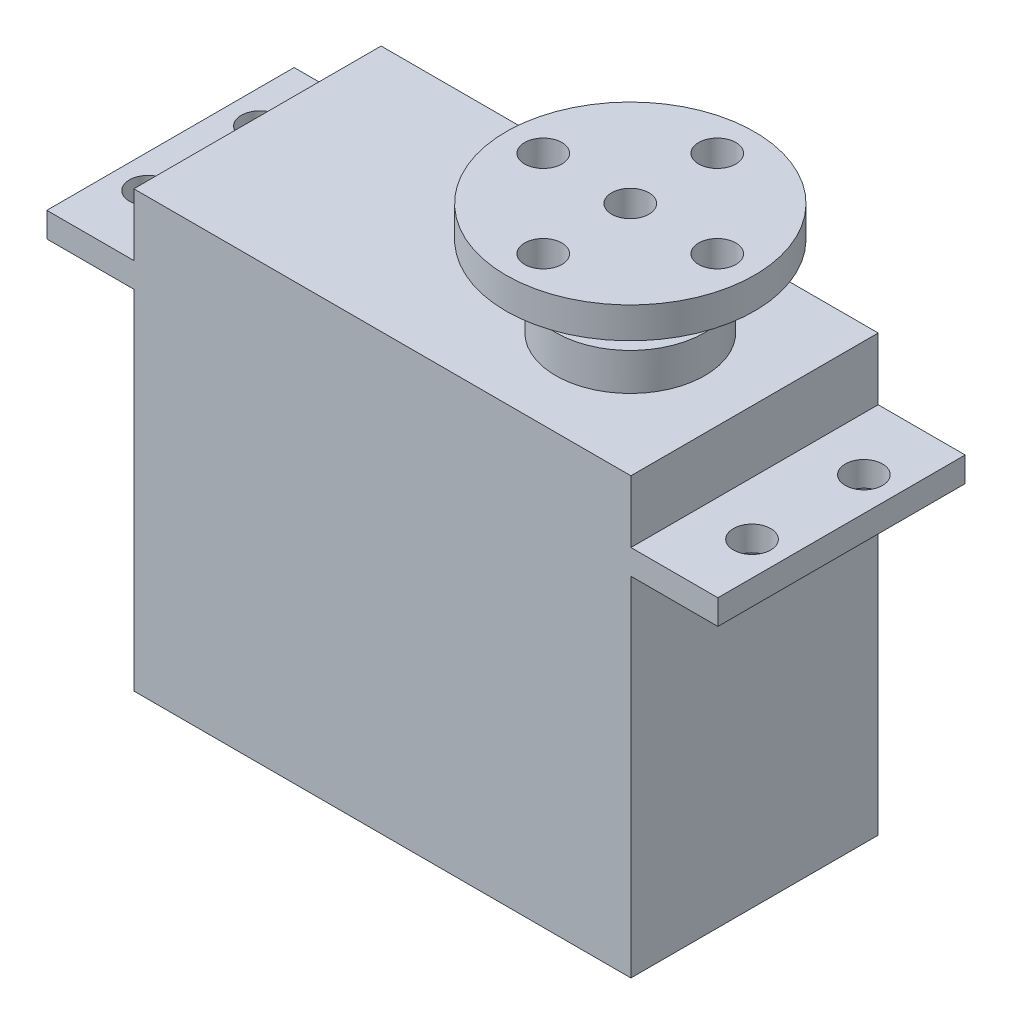
SolidWorks part; units mm, degrees
ref_plane "前视基准面" through (0, 0, 0) normal (0, 0, 1) x (1, 0, 0)
ref_plane "上视基准面" through (0, 0, 0) normal (0, 1, 0) x (1, 0, 0)
ref_plane "右视基准面" through (0, 0, 0) normal (1, 0, 0) x (0, 0, -1)
sketch "草图1" plane through (0, 0, 0) normal (0, 1, 0) x (1, 0, 0)
  line L1 (-20, -9.95) -> (20, -9.95)
  line L2 (-20, -9.95) -> (-20, 9.95)
  line L3 (-20, 9.95) -> (20, 9.95)
  line L4 (20, -9.95) -> (20, 9.95)
  line L5 (-20, -9.95) -> (20, 9.95) construction
  line L6 (-20, 9.95) -> (20, -9.95) construction
  point P0 (0, 0)
  dimension "D1" = 19.9
  dimension "D2" = 40
extrude "凸台-拉伸1" add sketch "草图1" along normal blind 28
sketch "草图2" plane through (0, 28, 0) normal (0, 1, 0) x (1, 0, 0)
  line L0 (20, 9.95) -> (-20, 9.95) construction
  line L1 (27, -9.95) -> (-27, -9.95)
  line L2 (27, -9.95) -> (27, 9.95)
  line L3 (27, 9.95) -> (-27, 9.95)
  line L4 (-27, -9.95) -> (-27, 9.95)
  line L5 (27, -9.95) -> (-27, 9.95) construction
  line L6 (27, 9.95) -> (-27, -9.95) construction
  point P0 (0, 0)
  dimension "D1" = 54
extrude "凸台-拉伸2" add sketch "草图2" along normal blind 2
sketch "草图3" plane through (0, 30, 0) normal (0, 1, 0) x (1, 0, 0)
  line L0 (27, 9.95) -> (-27, 9.95) construction
  line L1 (-20, -9.95) -> (20, -9.95)
  line L2 (-20, -9.95) -> (-20, 9.95)
  line L3 (-20, 9.95) -> (20, 9.95)
  line L4 (20, -9.95) -> (20, 9.95)
  line L5 (-20, -9.95) -> (20, 9.95) construction
  line L6 (-20, 9.95) -> (20, -9.95) construction
  line L8 (20, 9.95) -> (-20, 9.95) construction
  point P0 (0, 0)
extrude "凸台-拉伸3" add sketch "草图3" along normal blind 5
sketch "草图4" plane through (0, 30, 0) normal (0, 1, 0) x (1, 0, 0)
  line L0 (-27, 0) -> (49973, 0) construction
  line L1 (-27, 9.95) -> (-27, -9.95) construction
  circle A0 centre (-24.3, 4.5) radius 1.5
  circle A1 centre (24.3, 4.5) radius 1.5
  circle A2 centre (24.3, -4.5) radius 1.5
  circle A3 centre (-24.3, -4.5) radius 1.5
  point P15 (-27, 0)
  dimension "D1" = 3
  dimension "D2" = 3
  dimension "D3" = 24.3
  dimension "D4" = 24.3
  dimension "D5" = 4.5
  dimension "D6" = 4.5
extrude "切除-拉伸1" cut sketch "草图4" against normal through all
sketch "草图5" plane through (0, 35, 0) normal (0, 1, 0) x (1, 0, 0)
  line L0 (-20, 0) -> (20, 0) construction
  line L1 (-20, 9.95) -> (-20, -9.95) construction
  line L2 (20, -9.95) -> (20, 9.95) construction
  line L3 (-24.3, 6) -> (-24.3, -49994) construction
  circle A0 centre (10, 0) radius 3
  dimension "D1" = 6
  dimension "D2" = 34.3
extrude "凸台-拉伸4" add sketch "草图5" along normal blind 6.5
sketch "草图7" plane through (0, 35, 0) normal (0, 1, 0) x (1, 0, 0)
  circle A0 centre (10, 0) radius 6
  dimension "D1" = 12
extrude "凸台-拉伸5" add sketch "草图7" along normal blind 3
sketch "草图8" plane through (0, 41.5, 0) normal (0, 1, 0) x (1, 0, 0)
  circle A0 centre (10, 0) radius 4.5
  dimension "D1" = 9
extrude "凸台-拉伸6" add sketch "草图8" against normal blind 2
sketch "草图9" plane through (0, 41.5, 0) normal (0, 1, 0) x (1, 0, 0)
  circle A0 centre (10, 0) radius 10
  dimension "D1" = 20
extrude "凸台-拉伸7" add sketch "草图9" along normal blind 2.5
sketch "草图10" plane through (0, 44, 0) normal (0, 1, 0) x (1, 0, 0)
  circle A0 centre (10, 7) radius 1.5
  circle A1 centre (17, 0) radius 1.5
  circle A2 centre (10, -7) radius 1.5
  circle A3 centre (3, 0) radius 1.5
  point P2 (10, 0)
  point P13 (10, 0)
  dimension "D1" = 3
  dimension "D2" = 7
  dimension "D3" = 4
extrude "切除-拉伸2" cut sketch "草图10" against normal blind 2.5
sketch "草图11" plane through (0, 44, 0) normal (0, 1, 0) x (1, 0, 0)
  circle A0 centre (10, 0) radius 1.5
  dimension "D1" = 3
extrude "切除-拉伸3" cut sketch "草图11" against normal blind 6
